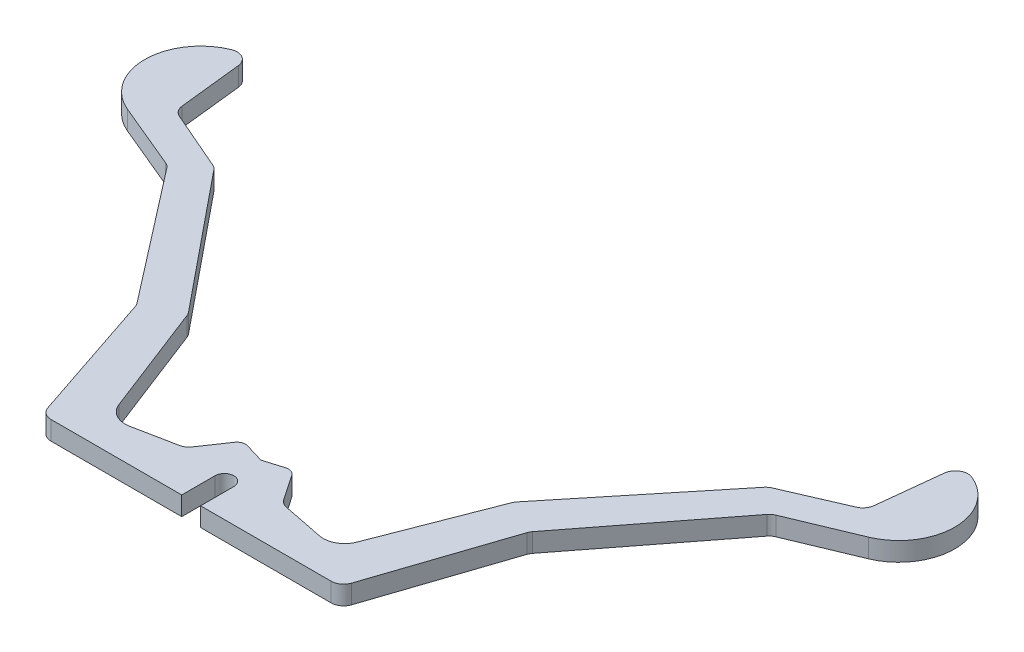
SolidWorks part; units mm, degrees
ref_plane "Front Plane" through (0, 0, 0) normal (0, 0, 1) x (1, 0, 0)
ref_plane "Top Plane" through (0, 0, 0) normal (0, 1, 0) x (1, 0, 0)
ref_plane "Right Plane" through (0, 0, 0) normal (1, 0, 0) x (0, 0, -1)
sketch "Sketch1" plane through (0, 0, 0) normal (0, 1, 0) x (1, 0, 0)
  line L0 (22.3003, 0) -> (1.5, 0)
  line L1 (0, 11.11) -> (3.0221, 12.0205)
  line L2 (4.5605, 11.4756) -> (7.2799, 7.4766)
  line L3 (8.5425, 6.6399) -> (15.11, 5.33)
  line L4 (18.9621, 7.4441) -> (25.8526, 25.2058)
  line L5 (24.1969, 1.3653) -> (31.2024, 22.2986)
  line L6 (31.5174, 22.888) -> (47.7964, 43.9219)
  line L7 (48.6079, 44.5436) -> (59.0492, 48.9)
  line L8 (44.5684, 48.0041) -> (53.9332, 52.0582)
  line L9 (55.1267, 53.6756) -> (56.2333, 63.77)
  line L10 (26.1659, 25.7448) -> (43.8116, 47.431)
  line L11 (-1.5, 0) -> (-1.5, 5.3)
  line L12 (1.5, 5.3) -> (1.5, 0)
  line L13 (0, -2.475) -> (0, 2.475) construction
  line L14 (-26.1659, 25.7448) -> (-43.8116, 47.431)
  line L15 (-55.1267, 53.6756) -> (-56.2333, 63.77)
  line L16 (-44.5684, 48.0041) -> (-53.9332, 52.0582)
  line L17 (-48.6079, 44.5436) -> (-59.0492, 48.9)
  line L18 (-31.5174, 22.888) -> (-47.7964, 43.9219)
  line L19 (-24.1969, 1.3653) -> (-31.2024, 22.2986)
  line L20 (-18.9621, 7.4441) -> (-25.8526, 25.2058)
  line L21 (-8.5425, 6.6399) -> (-15.11, 5.33)
  line L22 (-4.5605, 11.4756) -> (-7.2799, 7.4766)
  line L23 (0, 11.11) -> (-3.0221, 12.0205)
  line L24 (-22.3003, 0) -> (-1.5, 0)
  arc A0 (3.0221, 12.0205) -> (4.5605, 11.4756) centre (3.42, 10.7) cw
  arc A1 (15.11, 5.33) -> (18.9621, 7.4441) centre (15.778, 8.6793) ccw
  arc A2 (59.0492, 48.9) -> (58.9749, 65.4047) centre (55.6124, 57.137) ccw
  arc A3 (-59.0492, 48.9) -> (-58.9749, 65.4047) centre (-55.6124, 57.137) cw
  arc A4 (-15.11, 5.33) -> (-18.9621, 7.4441) centre (-15.778, 8.6793) cw
  arc A5 (-3.0221, 12.0205) -> (-4.5605, 11.4756) centre (-3.42, 10.7) ccw
  arc A6 (-1.5, 5.3) -> (1.5, 5.3) centre (0, 5.3) cw
  arc A7 (-58.9749, 65.4047) -> (-56.2333, 63.77) centre (-58.2214, 63.552) cw
  arc A8 (-55.1267, 53.6756) -> (-53.9332, 52.0582) centre (-53.1386, 53.8936) ccw
  arc A9 (47.7964, 43.9219) -> (48.6079, 44.5436) centre (49.3781, 42.6978) cw
  arc A10 (-48.6079, 44.5436) -> (-47.7964, 43.9219) centre (-49.3781, 42.6978) cw
  arc A11 (-43.8116, 47.431) -> (-44.5684, 48.0041) centre (-45.3629, 46.1687) ccw
  arc A12 (-31.5174, 22.888) -> (-31.2024, 22.2986) centre (-33.0991, 21.6639) cw
  arc A13 (-26.1659, 25.7448) -> (-25.8526, 25.2058) centre (-27.7172, 24.4825) cw
  arc A14 (31.2024, 22.2986) -> (31.5174, 22.888) centre (33.0991, 21.6639) cw
  arc A15 (-8.5425, 6.6399) -> (-7.2799, 7.4766) centre (-8.9337, 8.6013) ccw
  arc A16 (7.2799, 7.4766) -> (8.5425, 6.6399) centre (8.9337, 8.6013) ccw
  arc A17 (25.8526, 25.2058) -> (26.1659, 25.7448) centre (27.7172, 24.4825) cw
  arc A18 (58.9749, 65.4047) -> (56.2333, 63.77) centre (58.2214, 63.552) ccw
  arc A19 (53.9332, 52.0582) -> (55.1267, 53.6756) centre (53.1386, 53.8936) ccw
  arc A20 (44.5684, 48.0041) -> (43.8116, 47.431) centre (45.3629, 46.1687) ccw
  arc A21 (-24.1969, 1.3653) -> (-22.3003, 0) centre (-22.3003, 2) ccw
  arc A22 (22.3003, 0) -> (24.1969, 1.3653) centre (22.3003, 2) ccw
  point P17 (45.2391, 48.1972)
  point P18 (0, 0)
  point P19 (0, 0)
  point P20 (41.8043, 41.2941)
  point P22 (27.525, 27.0932)
  point P23 (0, 0)
  point P26 (0, 0)
  point P27 (0, 6.8)
  point P28 (25.3326, 23.6762)
  point P29 (0, 0)
  point P30 (25.9938, 25.5496)
  point P39 (3.8806, 12)
  point P49 (17.4212, 5.6853)
  point P53 (-56.48, 66.02)
  point P59 (-55, 52.52)
  point P62 (48.12, 44.34)
  point P65 (-48.12, 44.34)
  point P68 (-44.12, 47.81)
  point P71 (-31.31, 22.62)
  point P74 (-25.9667, 25.5)
  point P77 (31.31, 22.62)
  point P80 (-7.74, 6.8)
  point P83 (7.74, 6.8)
  point P86 (25.9667, 25.5)
  point P89 (56.48, 66.02)
  point P92 (55, 52.52)
  point P95 (44.12, 47.81)
  point P98 (-23.74, 0)
  point P101 (23.74, 0)
  point P102 (0, 0)
  dimension "D3" = 1.5
  dimension "D5" = 15.11
  dimension "D11" = 12
  dimension "D26" = 8.9252
  dimension "D27" = 2
  dimension "D2" = 22.24
  dimension "D4" = 6.8
  dimension "D6" = 6.07
  dimension "D7" = 29.81
  dimension "D8" = 4.31
  dimension "D9" = 7.74
  dimension "D10" = 5.33
  dimension "D12" = 3.42
  dimension "D13" = 5.4
  dimension "D14" = 22.62
  dimension "D15" = 66.02
  dimension "D16" = 8.5
  dimension "D17" = 46.62
  dimension "D18" = 44.34
  dimension "D19" = 42.62
  dimension "D20" = 47.81
  dimension "D21" = 53.5
  dimension "D22" = 52.52
  dimension "D23" = 17.12
  dimension "D24" = 54.98
  dimension "D25" = 25.5
extrude "Boss-Extrude16" add sketch "Sketch1" along normal blind 3
